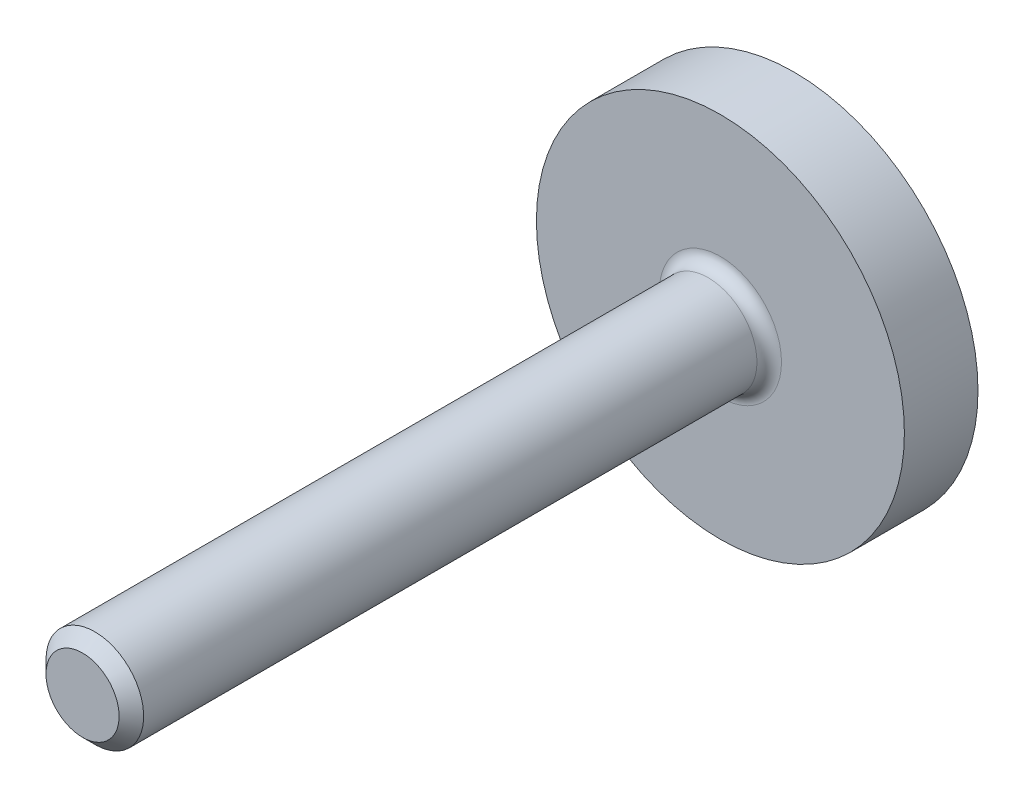
SolidWorks part; units mm, degrees
ref_plane "Front Plane" through (0, 0, 0) normal (0, 0, 1) x (1, 0, 0)
ref_plane "Top Plane" through (0, 0, 0) normal (0, 1, 0) x (1, 0, 0)
ref_plane "Right Plane" through (0, 0, 0) normal (1, 0, 0) x (0, 0, -1)
sketch "Sketch1" plane through (0, 0, 0) normal (0, 0, 1) x (1, 0, 0)
  circle A0 centre (0, 0) radius 7.5
  dimension "D1" = 15
extrude "Boss-Extrude1" add sketch "Sketch1" along normal blind 3
sketch "Sketch2" plane through (0, 0, 3) normal (0, 0, 1) x (1, 0, 0)
  circle A0 centre (0, 0) radius 1.99
  dimension "D1" = 3.98
extrude "Boss-Extrude2" add sketch "Sketch2" along normal blind 26
chamfer "Chamfer1" distance 0.5 angle 45 1 edges at (1.99, 0, 29)
fillet "Fillet1" radius 0.5 1 edges at (1.99, 0, 3)
